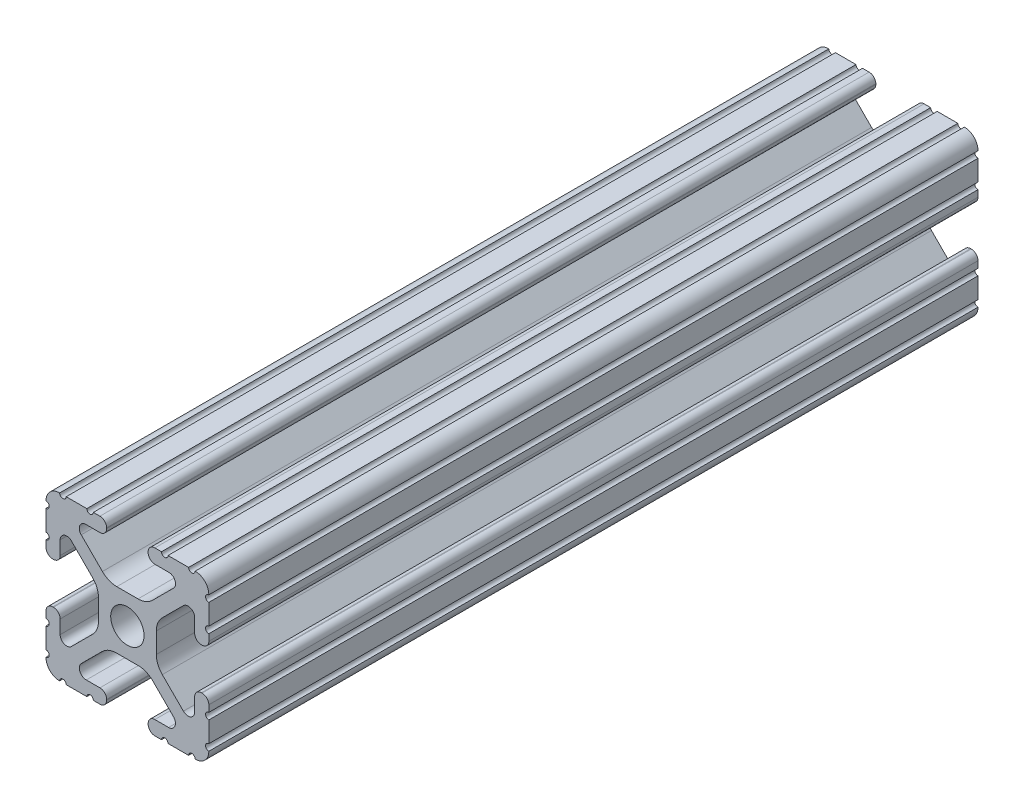
SolidWorks part; units mm, degrees
ref_plane "Front Plane" through (0, 0, 0) normal (0, 0, 1) x (1, 0, 0)
ref_plane "Top Plane" through (0, 0, 0) normal (0, 1, 0) x (1, 0, 0)
ref_plane "Right Plane" through (0, 0, 0) normal (1, 0, 0) x (0, 0, -1)
sketch "Sketch1" plane through (0, 0, 0) normal (0, 0, 1) x (1, 0, 0)
  line L88 (-7.1797, -8.6452) -> (-3.9523, -5.4237)
  line L89 (-1.7093, -4.4958) -> (1.7093, -4.4958)
  line L90 (3.9523, -5.4237) -> (7.1797, -8.6452)
  line L91 (6.4164, -10.4902) -> (4.2875, -10.4902)
  line L92 (3.2385, -11.5392) -> (3.2385, -11.651)
  line L93 (4.2875, -12.7) -> (5.3171, -12.7)
  line L94 (6.3331, -12.7) -> (9.5504, -12.7)
  line L95 (12.7, -9.5504) -> (12.7, -6.3331)
  line L96 (12.7, -5.3171) -> (12.7, -4.2875)
  line L97 (11.651, -3.2385) -> (11.5392, -3.2385)
  line L98 (10.4902, -4.2875) -> (10.4902, -6.4021)
  line L99 (8.7371, -7.1294) -> (5.441, -3.8408)
  line L100 (4.5085, -1.5932) -> (4.5085, 1.5932)
  line L101 (5.441, 3.8408) -> (8.7371, 7.1294)
  line L102 (10.4902, 6.4021) -> (10.4902, 4.2875)
  line L103 (11.5392, 3.2385) -> (11.651, 3.2385)
  line L104 (12.7, 4.2875) -> (12.7, 5.3171)
  line L105 (12.7, 6.3331) -> (12.7, 9.5504)
  line L106 (9.5504, 12.7) -> (6.3331, 12.7)
  line L107 (5.3171, 12.7) -> (4.2875, 12.7)
  line L108 (3.2385, 11.651) -> (3.2385, 11.5392)
  line L109 (4.2875, 10.4902) -> (6.4768, 10.4902)
  line L110 (7.207, 8.7244) -> (3.8983, 5.4232)
  line L111 (1.6558, 4.4958) -> (-1.6558, 4.4958)
  line L112 (-3.8983, 5.4232) -> (-7.207, 8.7244)
  line L113 (-6.4768, 10.4902) -> (-4.2875, 10.4902)
  line L114 (-3.2385, 11.5392) -> (-3.2385, 11.651)
  line L115 (-4.2875, 12.7) -> (-5.3171, 12.7)
  line L116 (-6.3331, 12.7) -> (-9.5504, 12.7)
  line L117 (-12.7, 9.5504) -> (-12.7, 6.3331)
  line L118 (-12.7, 5.3171) -> (-12.7, 4.2875)
  line L119 (-11.651, 3.2385) -> (-11.5392, 3.2385)
  line L120 (-10.4902, 4.2875) -> (-10.4902, 6.4021)
  line L121 (-8.7371, 7.1294) -> (-5.441, 3.8408)
  line L122 (-4.5085, 1.5932) -> (-4.5085, -1.5932)
  line L123 (-5.441, -3.8408) -> (-8.7371, -7.1294)
  line L124 (-10.4902, -6.4021) -> (-10.4902, -4.2875)
  line L125 (-11.5392, -3.2385) -> (-11.651, -3.2385)
  line L126 (-12.7, -4.2875) -> (-12.7, -5.3171)
  line L127 (-12.7, -6.3331) -> (-12.7, -9.5504)
  line L128 (-9.5504, -12.7) -> (-6.3331, -12.7)
  line L129 (-5.3171, -12.7) -> (-4.2875, -12.7)
  line L130 (-3.2385, -11.651) -> (-3.2385, -11.5392)
  line L131 (-4.2875, -10.4902) -> (-6.4164, -10.4902)
  circle A1 centre (0, 0) radius 2.6035
  arc A104 (-7.1797, -8.6452) -> (-6.4164, -10.4902) centre (-6.4164, -9.4098) ccw
  arc A105 (-1.7093, -4.4958) -> (-3.9523, -5.4237) centre (-1.7093, -7.6708) ccw
  arc A106 (3.9523, -5.4237) -> (1.7093, -4.4958) centre (1.7093, -7.6708) ccw
  arc A107 (6.4164, -10.4902) -> (7.1797, -8.6452) centre (6.4164, -9.4098) ccw
  arc A108 (4.2875, -10.4902) -> (3.2385, -11.5392) centre (4.2875, -11.5392) ccw
  arc A109 (3.2385, -11.651) -> (4.2875, -12.7) centre (4.2875, -11.651) ccw
  arc A110 (6.3331, -12.7) -> (5.3171, -12.7) centre (5.8251, -12.7) ccw
  arc A111 (10.5664, -12.6998) -> (9.5504, -12.7) centre (10.0584, -12.7) ccw
  arc A112 (10.5664, -12.6998) -> (12.6998, -10.5664) centre (10.5918, -10.5918) ccw
  arc A113 (12.7, -9.5504) -> (12.6998, -10.5664) centre (12.7, -10.0584) ccw
  arc A114 (12.7, -5.3171) -> (12.7, -6.3331) centre (12.7, -5.8251) ccw
  arc A115 (12.7, -4.2875) -> (11.651, -3.2385) centre (11.651, -4.2875) ccw
  arc A116 (11.5392, -3.2385) -> (10.4902, -4.2875) centre (11.5392, -4.2875) ccw
  arc A117 (8.7371, -7.1294) -> (10.4902, -6.4021) centre (9.4628, -6.4021) ccw
  arc A118 (4.5085, -1.5932) -> (5.441, -3.8408) centre (7.6835, -1.5932) ccw
  arc A119 (5.441, 3.8408) -> (4.5085, 1.5932) centre (7.6835, 1.5932) ccw
  arc A120 (10.4902, 6.4021) -> (8.7371, 7.1294) centre (9.4628, 6.4021) ccw
  arc A121 (10.4902, 4.2875) -> (11.5392, 3.2385) centre (11.5392, 4.2875) ccw
  arc A122 (11.651, 3.2385) -> (12.7, 4.2875) centre (11.651, 4.2875) ccw
  arc A123 (12.7, 6.3331) -> (12.7, 5.3171) centre (12.7, 5.8251) ccw
  arc A124 (12.6998, 10.5664) -> (12.7, 9.5504) centre (12.7, 10.0584) ccw
  arc A125 (12.6998, 10.5664) -> (10.5664, 12.6998) centre (10.5918, 10.5918) ccw
  arc A126 (9.5504, 12.7) -> (10.5664, 12.6998) centre (10.0584, 12.7) ccw
  arc A127 (5.3171, 12.7) -> (6.3331, 12.7) centre (5.8251, 12.7) ccw
  arc A128 (4.2875, 12.7) -> (3.2385, 11.651) centre (4.2875, 11.651) ccw
  arc A129 (3.2385, 11.5392) -> (4.2875, 10.4902) centre (4.2875, 11.5392) ccw
  arc A130 (7.207, 8.7244) -> (6.4768, 10.4902) centre (6.4768, 9.4563) ccw
  arc A131 (1.6558, 4.4958) -> (3.8983, 5.4232) centre (1.6558, 7.6708) ccw
  arc A132 (-3.8983, 5.4232) -> (-1.6558, 4.4958) centre (-1.6558, 7.6708) ccw
  arc A133 (-6.4768, 10.4902) -> (-7.207, 8.7244) centre (-6.4768, 9.4563) ccw
  arc A134 (-4.2875, 10.4902) -> (-3.2385, 11.5392) centre (-4.2875, 11.5392) ccw
  arc A135 (-3.2385, 11.651) -> (-4.2875, 12.7) centre (-4.2875, 11.651) ccw
  arc A136 (-6.3331, 12.7) -> (-5.3171, 12.7) centre (-5.8251, 12.7) ccw
  arc A137 (-10.5664, 12.6998) -> (-9.5504, 12.7) centre (-10.0584, 12.7) ccw
  arc A138 (-10.5664, 12.6998) -> (-12.6998, 10.5664) centre (-10.5918, 10.5918) ccw
  arc A139 (-12.7, 9.5504) -> (-12.6998, 10.5664) centre (-12.7, 10.0584) ccw
  arc A140 (-12.7, 5.3171) -> (-12.7, 6.3331) centre (-12.7, 5.8251) ccw
  arc A141 (-12.7, 4.2875) -> (-11.651, 3.2385) centre (-11.651, 4.2875) ccw
  arc A142 (-11.5392, 3.2385) -> (-10.4902, 4.2875) centre (-11.5392, 4.2875) ccw
  arc A143 (-8.7371, 7.1294) -> (-10.4902, 6.4021) centre (-9.4628, 6.4021) ccw
  arc A144 (-4.5085, 1.5932) -> (-5.441, 3.8408) centre (-7.6835, 1.5932) ccw
  arc A145 (-5.441, -3.8408) -> (-4.5085, -1.5932) centre (-7.6835, -1.5932) ccw
  arc A146 (-10.4902, -6.4021) -> (-8.7371, -7.1294) centre (-9.4628, -6.4021) ccw
  arc A147 (-10.4902, -4.2875) -> (-11.5392, -3.2385) centre (-11.5392, -4.2875) ccw
  arc A148 (-11.651, -3.2385) -> (-12.7, -4.2875) centre (-11.651, -4.2875) ccw
  arc A149 (-12.7, -6.3331) -> (-12.7, -5.3171) centre (-12.7, -5.8251) ccw
  arc A150 (-12.6998, -10.5664) -> (-12.7, -9.5504) centre (-12.7, -10.0584) ccw
  arc A151 (-12.6998, -10.5664) -> (-10.5664, -12.6998) centre (-10.5918, -10.5918) ccw
  arc A152 (-9.5504, -12.7) -> (-10.5664, -12.6998) centre (-10.0584, -12.7) ccw
  arc A153 (-5.3171, -12.7) -> (-6.3331, -12.7) centre (-5.8251, -12.7) ccw
  arc A154 (-4.2875, -12.7) -> (-3.2385, -11.651) centre (-4.2875, -11.651) ccw
  arc A155 (-3.2385, -11.5392) -> (-4.2875, -10.4902) centre (-4.2875, -11.5392) ccw
extrude "Boss-Extrude1" add sketch "Sketch1" along normal mid plane 120
